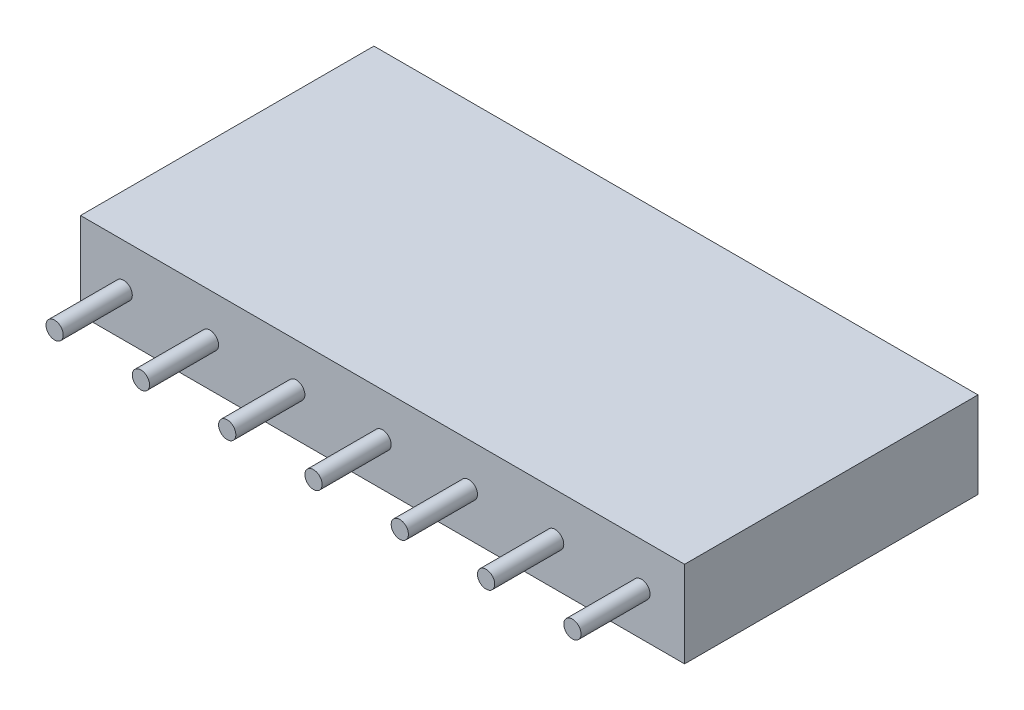
SolidWorks part; units mm, degrees
ref_plane "Plan de face" through (0, 0, 0) normal (0, 0, 1) x (1, 0, 0)
ref_plane "Plan de dessus" through (0, 0, 0) normal (0, 1, 0) x (1, 0, 0)
ref_plane "Plan de droite" through (0, 0, 0) normal (1, 0, 0) x (0, 0, -1)
sketch "Esquisse1" plane through (0, 0, 0) normal (0, 0, 1) x (1, 0, 0)
  line L1 (0, 0) -> (-2.5, 0)
  line L2 (0, 0) -> (0, 2.5)
  line L3 (0, 2.5) -> (-2.5, 2.5)
  line L4 (-2.5, 0) -> (-2.5, 2.5)
  dimension "D1" = 2.5
  dimension "D2" = 2.5
extrude "Boss.-Extru.1" add sketch "Esquisse1" along normal blind 8.5
sketch "Esquisse2" plane through (0, 0, 8.5) normal (0, 0, 1) x (1, 0, 0)
  line L0 (-2.5, 2.5) -> (0, 0) construction
  circle A0 centre (-1.25, 1.25) radius 0.25
  dimension "D1" = 0.5
extrude "Boss.-Extru.2" add sketch "Esquisse2" along normal blind 2
sketch "Esquisse3" plane through (0, 0, 0) normal (0, 0, -1) x (-1, 0, 0)
  line L0 (0, 2.5) -> (2.5, 0) construction
  circle A0 centre (1.25, 1.25) radius 0.25
  dimension "D1" = 0.5
extrude "Enlèv. mat.-Extru.2" cut sketch "Esquisse3" against normal blind 4
pattern_linear "Répétition linéaire1" count 7 spacing 2.5 along (-1, 0, 0) of "Boss.-Extru.1", "Enlèv. mat.-Extru.2", "Boss.-Extru.2"
